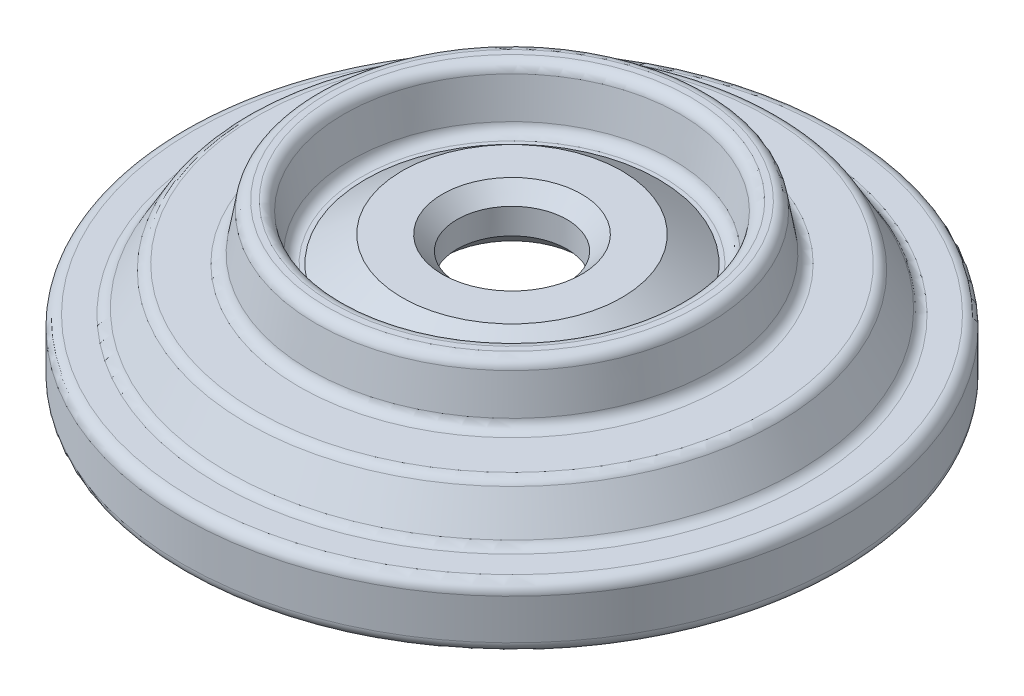
SolidWorks part; units mm, degrees
ref_plane "前视基准面" through (0, 0, 0) normal (0, 0, 1) x (1, 0, 0)
ref_plane "上视基准面" through (0, 0, 0) normal (0, 1, 0) x (1, 0, 0)
ref_plane "右视基准面" through (0, 0, 0) normal (1, 0, 0) x (0, 0, -1)
other "Configuration Table"
sketch "草图1" plane through (0, 0, 0) normal (0, 0, 1) x (1, 0, 0)
  line L0 (0, 85.7031) -> (0, -79.9219) construction
  line L1 (-15, 15) -> (-15, 0)
  line L2 (-15, 0) -> (-66.8812, 0)
  line L3 (-66.8812, 0) -> (-79.0056, -21)
  line L4 (-79.0056, -21) -> (-87, -21)
  line L5 (-90, -18) -> (-90, -7)
  line L6 (-87, -4) -> (-80.1603, -4)
  line L7 (-77.5622, -2.5) -> (-72.366, 6.5)
  line L8 (-69.7679, 8) -> (-58.1622, 8)
  line L9 (-55.2078, 10.4791) -> (-53.4371, 20.5209)
  line L10 (-50.4827, 23) -> (-48.8071, 23)
  line L11 (-45.8527, 20.5209) -> (-44.082, 10.4791)
  line L12 (-41.1276, 8) -> (-39.997, 8)
  line L13 (-39.997, 8) -> (-30, 15)
  line L14 (-30, 15) -> (-15, 15)
  line L15 (-49.6449, 37.8009) -> (-49.6449, 4.4058) construction
  arc A0 (-80.1603, -4) -> (-77.5622, -2.5) centre (-80.1603, -1) ccw
  arc A1 (-44.082, 10.4791) -> (-41.1276, 8) centre (-41.1276, 11) ccw
  arc A2 (-58.1622, 8) -> (-55.2078, 10.4791) centre (-58.1622, 11) ccw
  arc A3 (-48.8071, 23) -> (-45.8527, 20.5209) centre (-48.8071, 20) cw
  arc A4 (-53.4371, 20.5209) -> (-50.4827, 23) centre (-50.4827, 20) cw
  arc A5 (-72.366, 6.5) -> (-69.7679, 8) centre (-69.7679, 5) cw
  arc A6 (-90, -7) -> (-87, -4) centre (-87, -7) cw
  arc A7 (-87, -21) -> (-90, -18) centre (-87, -18) cw
  point P11 (-37.5912, 8)
  point P24 (-43.6449, 8)
  point P27 (-55.6449, 8)
  point P32 (-53, 23)
  point P35 (-71.5, 8)
  dimension "D17" = 3
  dimension "D1" = 30
  dimension "D2" = 60
  dimension "D3" = 106
  dimension "D4" = 180
  dimension "D5" = 17
  dimension "D6" = 8
  dimension "D7" = 8
  dimension "D8" = 8
  dimension "D9" = 12
  dimension "D10" = 20
  dimension "D11" = 120
  dimension "D12" = 15
  dimension "D13" = 44
  dimension "D14" = 45
  dimension "D15" = 143
  dimension "D16" = 15
revolve "旋转1" add sketch "草图1" angle 360 about L0
chamfer "倒角2" distance 4 angle 45 2 edges at (0, 0, 15) (0, 15, 15)
